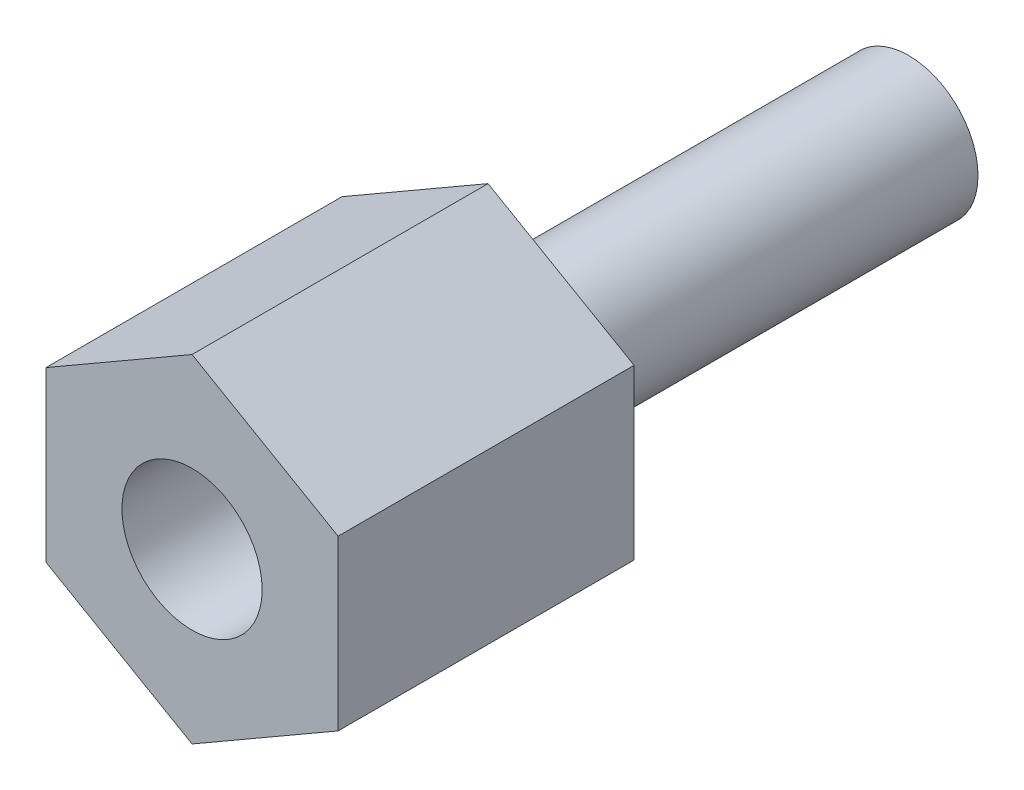
SolidWorks part; units mm, degrees
ref_plane "Front Plane" through (0, 0, 0) normal (0, 0, 1) x (1, 0, 0)
ref_plane "Top Plane" through (0, 0, 0) normal (0, 1, 0) x (1, 0, 0)
ref_plane "Right Plane" through (0, 0, 0) normal (1, 0, 0) x (0, 0, -1)
sketch "Sketch1" plane through (0, 0, 0) normal (0, 0, 1) x (1, 0, 0)
  line L1 (0, 2.7496) -> (-2.3812, 1.3748)
  line L2 (-2.3812, 1.3748) -> (-2.3812, -1.3748)
  line L3 (-2.3812, -1.3748) -> (0, -2.7496)
  line L4 (0, -2.7496) -> (2.3813, -1.3748)
  line L5 (2.3813, -1.3748) -> (2.3812, 1.3748)
  line L6 (2.3812, 1.3748) -> (0, 2.7496)
  circle A0 centre (0, 0) radius 2.3812 construction
  dimension "D1" = 4.7625
extrude "Boss-Extrude1" add sketch "Sketch1" along normal blind 4.826
sketch "Sketch2" plane through (0, 0, 0) normal (0, 0, -1) x (-1, 0, 0)
  circle A0 centre (0, 0) radius 1.1303
  dimension "D1" = 2.2606
extrude "Boss-Extrude2" add sketch "Sketch2" along normal blind 6.858
sketch "Sketch3" plane through (0, 0, 4.826) normal (0, 0, 1) x (1, 0, 0)
  circle A0 centre (0, 0) radius 1.143
  dimension "D1" = 2.286
extrude "Cut-Extrude1" cut sketch "Sketch3" against normal blind 2.54
